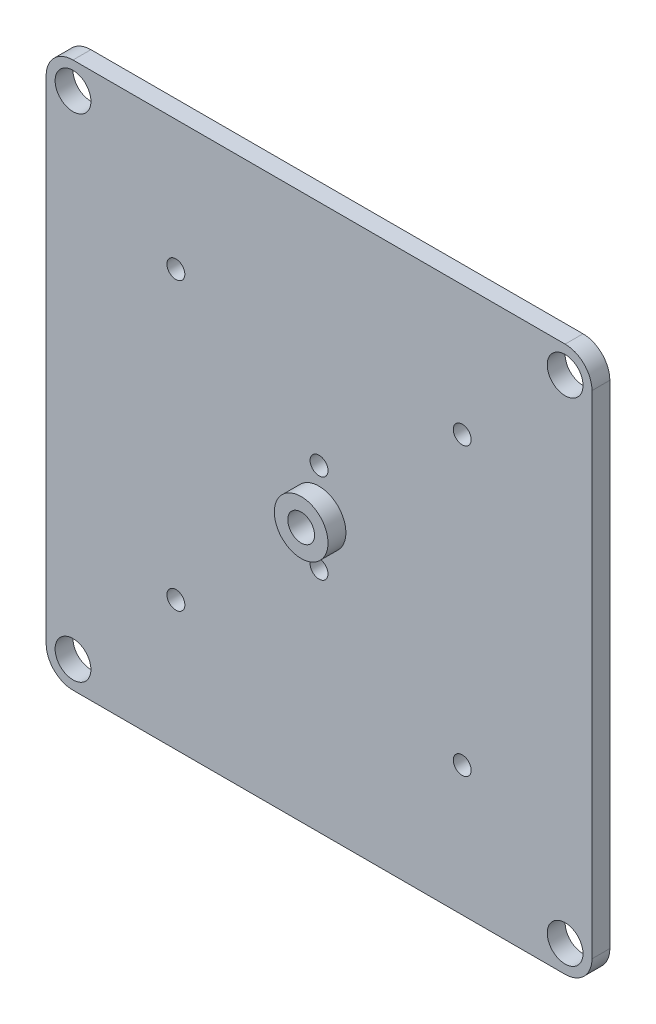
SolidWorks part; units mm, degrees
ref_plane "Plan de face" through (0, 0, 0) normal (0, 0, 1) x (1, 0, 0)
ref_plane "Plan de dessus" through (0, 0, 0) normal (0, 1, 0) x (1, 0, 0)
ref_plane "Plan de droite" through (0, 0, 0) normal (1, 0, 0) x (0, 0, -1)
sketch "Esquisse1" plane through (0, 0, 0) normal (0, 0, 1) x (1, 0, 0)
  line L1 (-152.5, -152.5) -> (152.5, -152.5)
  line L2 (-152.5, -152.5) -> (-152.5, 152.5)
  line L3 (-152.5, 152.5) -> (152.5, 152.5)
  line L4 (152.5, -152.5) -> (152.5, 152.5)
  dimension "D1" = 152.5
  dimension "D2" = 305
  dimension "D3" = 305
  dimension "D4" = 152.5
extrude "Boss.-Extru.1" add sketch "Esquisse1" along normal blind 10
sketch "Esquisse2" plane through (0, 0, 10) normal (0, 0, 1) x (1, 0, 0)
  line L0 (152.5, 152.5) -> (-152.5, 152.5) construction
  line L1 (152.5, -152.5) -> (152.5, 152.5) construction
  line L2 (-152.5, 152.5) -> (-152.5, -152.5) construction
  line L3 (-152.5, -152.5) -> (152.5, -152.5) construction
  circle A0 centre (137.5, 137.5) radius 15 construction
  circle A1 centre (137.5, -137.5) radius 15 construction
  circle A2 centre (-137.5, -137.5) radius 15 construction
  circle A3 centre (-137.5, 137.5) radius 15 construction
  circle A4 centre (137.5, 137.5) radius 10
  circle A5 centre (137.5, -137.5) radius 10
  circle A6 centre (-137.5, -137.5) radius 10
  circle A7 centre (-137.5, 137.5) radius 10
  dimension "D1" = 30
  dimension "3" = 30
  dimension "D2" = 30
  dimension "D3" = 30
  dimension "D4" = 20
  dimension "D5" = 20
  dimension "D6" = 20
  dimension "D7" = 20
extrude "Enlèv. mat.-Extru.10" cut sketch "Esquisse2" against normal blind 10
fillet "Congé2" radius 15 4 edges at (152.5, 152.5, 5) (152.5, -152.5, 5) (-152.5, -152.5, 5) (-152.5, 152.5, 5)
sketch "Esquisse3" plane through (0, 0, 10) normal (0, 0, 1) x (1, 0, 0)
  line L1 (-100, -100) -> (100, -100) construction
  line L2 (-100, -100) -> (-100, 100) construction
  line L3 (-100, 100) -> (100, 100) construction
  line L4 (100, -100) -> (100, 100) construction
  line L5 (-80, -80) -> (80, -80) construction
  line L6 (-80, -80) -> (-80, 80) construction
  line L7 (-80, 80) -> (80, 80) construction
  line L8 (80, -80) -> (80, 80) construction
  circle A0 centre (80, 80) radius 5
  circle A1 centre (80, -80) radius 5
  circle A2 centre (-80, -80) radius 5
  circle A3 centre (-80, 80) radius 5
  point P4 (0, 0)
  dimension "D9" = 10
  dimension "D10" = 10
  dimension "D11" = 10
  dimension "D12" = 10
  dimension "D1" = 200
  dimension "D2" = 200
  dimension "D3" = 100
  dimension "D4" = 100
  dimension "D5" = 20
  dimension "D6" = 20
  dimension "D7" = 20
  dimension "D8" = 20
extrude "Enlèv. mat.-Extru.11" cut sketch "Esquisse3" against normal blind 10
sketch "Esquisse4" plane through (0, 0, 10) normal (0, 0, 1) x (1, 0, 0)
  circle A0 centre (0, 0) radius 15
  dimension "D1" = 30
extrude "Boss.-Extru.2" add sketch "Esquisse4" along normal blind 10
sketch "Esquisse5" plane through (0, 0, 20) normal (0, 0, 1) x (1, 0, 0)
  circle A0 centre (0, 0) radius 7.5
  dimension "D1" = 15
extrude "Enlèv. mat.-Extru.12" cut sketch "Esquisse5" against normal blind 20
sketch "Esquisse6" plane through (0, 0, 10) normal (0, 0, 1) x (1, 0, 0)
  line L0 (0, 25) -> (0, -25) construction
  circle A2 centre (0, 25) radius 5
  circle A3 centre (0, -25) radius 5
  dimension "D3" = 10
  dimension "D4" = 10
  dimension "D1" = 50
  dimension "D2" = 25
extrude "Enlèv. mat.-Extru.13" cut sketch "Esquisse6" against normal blind 10
